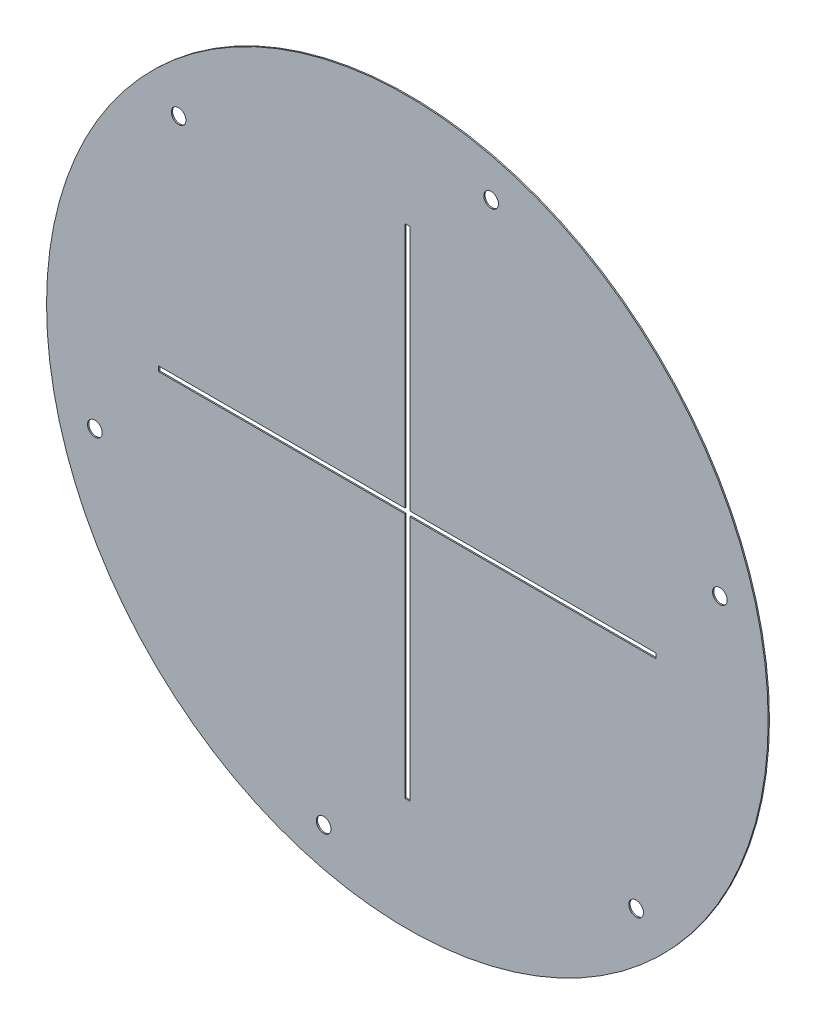
SolidWorks part; units mm, degrees
ref_plane "Front Plane" through (0, 0, 0) normal (0, 0, 1) x (1, 0, 0)
ref_plane "Top Plane" through (0, 0, 0) normal (0, 1, 0) x (1, 0, 0)
ref_plane "Right Plane" through (0, 0, 0) normal (1, 0, 0) x (0, 0, -1)
sketch "Sketch2" plane through (0, 0, 0) normal (0, 0, 1) x (1, 0, 0)
  line L0 (-0.5, 50) -> (-0.5, 0.5)
  line L9 (-0.5, 0.5) -> (-50, 0.5)
  line L10 (-50, 0.5) -> (-50, -0.5)
  line L11 (-50, -0.5) -> (-0.5, -0.5)
  line L12 (-0.5, -0.5) -> (-0.5, -50)
  line L13 (-0.5, -50) -> (0.5, -50)
  line L14 (0.5, -50) -> (0.5, -0.5)
  line L15 (0.5, -0.5) -> (50, -0.5)
  line L16 (50, -0.5) -> (50, 0.5)
  line L17 (50, 0.5) -> (0.5, 0.5)
  line L18 (0.5, 0.5) -> (0.5, 50)
  line L19 (0.5, 50) -> (-0.5, 50)
  line L20 (-72.5, 0) -> (72.5, 0) construction
  line L21 (0, 72.5) -> (0, -72.5) construction
  line L22 (-0.5, 0.5) -> (0.5, -0.5) construction
  line L23 (0.5, 0.5) -> (-0.5, -0.5) construction
  line L24 (-62.7852, -16.8232) -> (62.7852, 16.8232) construction
  line L25 (16.8232, 62.7852) -> (-16.8232, -62.7852) construction
  line L26 (45.9619, -45.9619) -> (-45.9619, 45.9619) construction
  circle A12 centre (0, 0) radius 72.5
  circle A13 centre (62.7852, 16.8232) radius 1.4732
  circle A14 centre (-62.7852, -16.8232) radius 1.4732
  circle A15 centre (16.8232, 62.7852) radius 1.4732
  circle A16 centre (-16.8232, -62.7852) radius 1.4732
  circle A17 centre (45.9619, -45.9619) radius 1.4732
  circle A18 centre (-45.9619, 45.9619) radius 1.4732
  point P21 (0, 0)
  point P22 (0, 0)
  point P23 (13.52, 3.6227)
  point P24 (0, 0)
  point P35 (0, 0)
  dimension "D3" = 3
  dimension "D1" = 15
  dimension "D9" = 145
  dimension "D2" = 2.9464
  dimension "D6" = 1
  dimension "D7" = 100
  dimension "D4" = 130
extrude "Boss-Extrude3" add sketch "Sketch2" along normal blind 0.254
